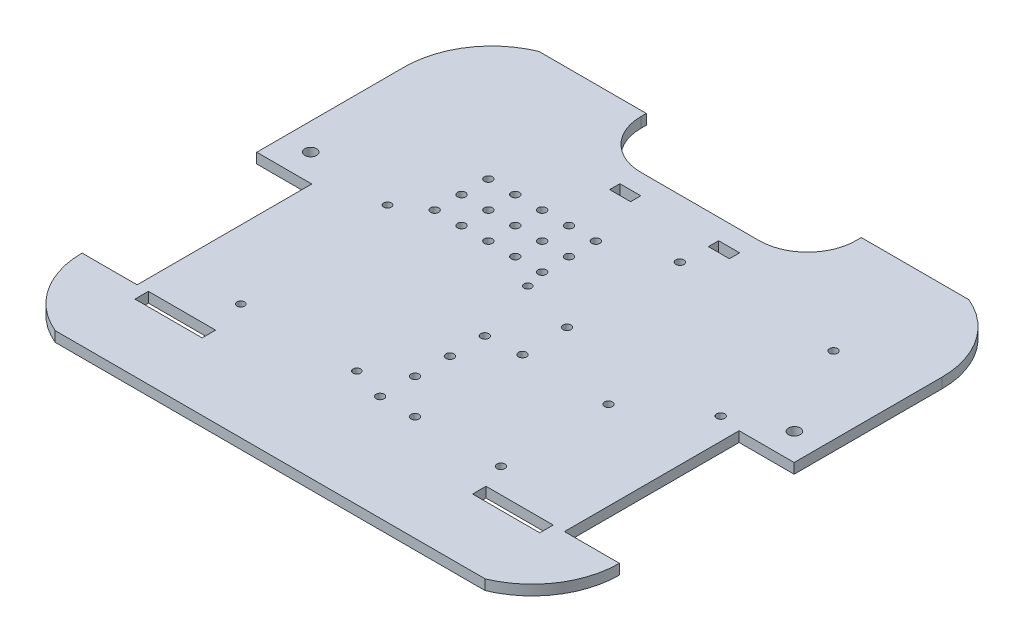
SolidWorks part; units mm, degrees
ref_plane "Front Plane" through (0, 0, 0) normal (0, 0, 1) x (1, 0, 0)
ref_plane "Top Plane" through (0, 0, 0) normal (0, 1, 0) x (1, 0, 0)
ref_plane "Right Plane" through (0, 0, 0) normal (1, 0, 0) x (0, 0, -1)
sketch "Sketch1" plane through (0, 0, 0) normal (0, 1, 0) x (1, 0, 0)
  line L1 (-127, 114.3) -> (127, 114.3)
  line L2 (-127, 114.3) -> (-127, -114.3)
  line L3 (-127, -114.3) -> (127, -114.3)
  line L4 (127, 114.3) -> (127, -114.3)
  line L5 (-127, 114.3) -> (127, -114.3) construction
  line L6 (-127, -114.3) -> (127, 114.3) construction
  point P0 (0, 0)
  dimension "D1" = 254
  dimension "D2" = 228.6
extrude "Boss-Extrude1" add sketch "Sketch1" along normal blind 4.826
sketch "Sketch2" plane through (0, 4.826, 0) normal (0, 1, 0) x (1, 0, 0)
  line L0 (-127, 114.3) -> (-127, -114.3) construction
  line L1 (-127, 6.35) -> (-101, 6.35)
  line L2 (-127, 6.35) -> (-127, -76.2)
  line L3 (-127, -76.2) -> (-101, -76.2)
  line L4 (-101, 6.35) -> (-101, -76.2)
  line L5 (127, -114.3) -> (127, 114.3) construction
  line L6 (127, 6.35) -> (101, 6.35)
  line L7 (127, 6.35) -> (127, -76.2)
  line L8 (127, -76.2) -> (101, -76.2)
  line L9 (101, 6.35) -> (101, -76.2)
  line L10 (-127, -114.3) -> (127, -114.3) construction
  dimension "D1" = 38.1
  dimension "D2" = 38.1
  dimension "D3" = 82.55
  dimension "D4" = 82.55
  dimension "D5" = 26
  dimension "D6" = 26
extrude "Cut-Extrude1" cut sketch "Sketch2" against normal blind 4.826
sketch "Sketch4" plane through (0, 4.826, 0) normal (0, 1, 0) x (1, 0, 0)
  line L0 (0, -114.3) -> (0, 114.3) construction
  line L1 (-127, -114.3) -> (127, -114.3) construction
  line L2 (127, 114.3) -> (-127, 114.3) construction
  line L3 (-127, 76.2) -> (-101.6, 76.2) construction
  line L4 (-127, 114.3) -> (-127, 6.35) construction
  line L5 (-101.6, 76.2) -> (-101.6, 114.3) construction
  line L6 (-127, 76.2) -> (-127, 114.3)
  line L7 (-127, 114.3) -> (-101.6, 114.3)
  line L8 (127, 76.2) -> (127, 114.3)
  line L9 (127, 114.3) -> (101.6, 114.3)
  arc A0 (-127, 76.2) -> (-101.6, 114.3) centre (-85.725, 76.2) cw
  arc A1 (127, 76.2) -> (101.6, 114.3) centre (85.725, 76.2) ccw
  dimension "D2" = 38.1
  dimension "D1" = 25.4
extrude "Cut-Extrude3" cut sketch "Sketch4" against normal blind 4.826
sketch "Sketch7" plane through (0, 4.826, 0) normal (0, 1, 0) x (1, 0, 0)
  line L0 (0, -114.3) -> (0, 114.3) construction
  line L1 (-127, -114.3) -> (127, -114.3) construction
  line L2 (101.6, 114.3) -> (-101.6, 114.3) construction
  line L3 (50.8, 88.9) -> (50.8, 114.3)
  line L4 (50.8, 88.9) -> (-50.8, 88.9)
  line L5 (0, 88.9) -> (0, 114.3)
  line L6 (50.8, 114.3) -> (-50.8, 114.3)
  line L7 (-50.8, 88.9) -> (-50.8, 114.3)
  line M6 (101.6, 114.3) -> (-101.6, 114.3)
  dimension "D1" = 25.4
  dimension "D2" = 50.8
extrude "Cut-Extrude5" cut sketch "Sketch7" against normal blind 4.826 contours L7 L4 L5 M6 | L5 L4 L3 M6
fillet "Fillet9" radius 22.86 1 edges at (-50.8, 2.413, -88.9)
fillet "Fillet10" radius 22.86 1 edges at (50.8, 2.413, -88.9)
sketch "Sketch8" plane through (0, 4.826, 0) normal (0, 1, 0) x (1, 0, 0)
  line L0 (-127, -76.2) -> (-101.6, -76.2) construction
  line L1 (-101.6, -76.2) -> (-101.6, -114.3) construction
  line L2 (-127, -114.3) -> (127, -114.3) construction
  line L3 (-127, -76.2) -> (-127, -114.3)
  line L4 (-127, -114.3) -> (-101.6, -114.3)
  line L5 (0, -114.3) -> (0, 88.9) construction
  line L6 (27.94, 88.9) -> (-27.94, 88.9) construction
  line L7 (127, -114.3) -> (101.6, -114.3)
  line L8 (127, -76.2) -> (127, -114.3)
  arc A0 (-127, -76.2) -> (-101.6, -114.3) centre (-85.725, -76.2) ccw
  arc A1 (127, -76.2) -> (101.6, -114.3) centre (85.725, -76.2) cw
  dimension "D1" = 25.4
extrude "Cut-Extrude6" cut sketch "Sketch8" against normal blind 4.826
sketch "Sketch9" plane through (0, 0, 0) normal (0, -1, 0) x (1, 0, 0)
  line L0 (-58.582, 76.2) -> (-101, 76.2) construction
  line L1 (-95.666, 76.2) -> (-63.916, 76.2)
  line L2 (-95.666, 76.2) -> (-95.666, 82.55)
  line L3 (-95.666, 82.55) -> (-63.916, 82.55)
  line L4 (-63.916, 76.2) -> (-63.916, 82.55)
  line L5 (-101, 76.2) -> (-95.666, 76.2) construction
  line L6 (-63.916, 76.2) -> (-58.582, 76.2) construction
  line L7 (0, 114.3) -> (0, -88.9) construction
  line L8 (-101.6, 114.3) -> (101.6, 114.3) construction
  line L9 (27.94, -88.9) -> (-27.94, -88.9) construction
  line L10 (63.916, 76.2) -> (58.582, 76.2) construction
  line L11 (101, 76.2) -> (95.666, 76.2) construction
  line L12 (63.916, 76.2) -> (63.916, 82.55)
  line L13 (95.666, 82.55) -> (63.916, 82.55)
  line L14 (95.666, 76.2) -> (95.666, 82.55)
  line L15 (95.666, 76.2) -> (63.916, 76.2)
  dimension "D1" = 31.75
  dimension "D2" = 6.35
extrude "Cut-Extrude7" cut sketch "Sketch9" against normal through all
sketch "Sketch11" plane through (0, 4.826, 0) normal (0, 1, 0) x (1, 0, 0)
  line L0 (-18.3929, 74.4508) -> (-28.2989, 74.4508) construction
  line L1 (-28.2989, 79.2768) -> (-28.2989, 74.4508) construction
  line L2 (-18.3929, 79.2768) -> (-28.2989, 79.2768) construction
  line L3 (-18.3929, 79.2768) -> (-18.3929, 74.4508) construction
  line L4 (28.2989, 74.4508) -> (18.3929, 74.4508) construction
  line L5 (18.3929, 79.2768) -> (18.3929, 74.4508) construction
  line L6 (28.2989, 79.2768) -> (18.3929, 79.2768) construction
  line L7 (28.2989, 79.2768) -> (28.2989, 74.4508) construction
  line L8 (-18.3929, 74.4508) -> (-28.2989, 74.4508)
  line L9 (-28.2989, 79.2768) -> (-28.2989, 74.4508)
  line L10 (-18.3929, 79.2768) -> (-28.2989, 79.2768)
  line L11 (-18.3929, 79.2768) -> (-18.3929, 74.4508)
  line L12 (28.2989, 74.4508) -> (18.3929, 74.4508)
  line L13 (18.3929, 79.2768) -> (18.3929, 74.4508)
  line L14 (28.2989, 79.2768) -> (18.3929, 79.2768)
  line L15 (28.2989, 79.2768) -> (28.2989, 74.4508)
extrude "Cut-Extrude8" cut sketch "Sketch11" against normal through all
sketch "Sketch13" plane through (0, 4.826, 0) normal (0, 1, 0) x (1, 0, 0)
  line L1 (-4.1249, -61.8428) -> (-4.1249, 17.9132) construction
  circle A0 centre (-10.4749, 24.7159) radius 1.905
  circle A1 centre (-23.1749, 24.7159) radius 1.905
  circle A2 centre (-35.8749, 24.7159) radius 1.905
  circle A3 centre (-48.5749, 24.7159) radius 1.905
  circle A4 centre (-61.2749, 24.7159) radius 1.905
  circle A5 centre (-23.1749, 37.4159) radius 1.905
  circle A6 centre (-35.8749, 37.4159) radius 1.905
  circle A7 centre (-48.5749, 37.4159) radius 1.905
  circle A8 centre (-61.2749, 37.4159) radius 1.905
  circle A9 centre (-23.1749, 50.1159) radius 1.905
  circle A10 centre (-35.8749, 50.1159) radius 1.905
  circle A11 centre (-48.5749, 50.1159) radius 1.905
  circle A12 centre (-61.2749, 50.1159) radius 1.905
  circle A13 centre (-10.4749, 37.4159) radius 1.905
  circle A14 centre (-10.4749, 50.1159) radius 1.905
  dimension "D1" = 3.81
  dimension "D4" = 6.35
  dimension "D2" = 5
  dimension "D3" = 3
extrude "Cut-Extrude10" cut sketch "Sketch13" against normal through all
sketch "Sketch14" plane through (0, 4.826, 0) normal (0, 1, 0) x (1, 0, 0)
  circle A0 centre (-68.6409, -59.5568) radius 1.778 construction
  circle A1 centre (-13.7769, -59.5568) radius 1.778 construction
  circle A2 centre (-74.4829, 15.6272) radius 1.778 construction
  circle A3 centre (-8.1889, 15.6272) radius 1.778 construction
  circle A4 centre (-68.6409, -59.5568) radius 1.778
  circle A5 centre (-13.7769, -59.5568) radius 1.778
  circle A6 centre (-74.4829, 15.6272) radius 1.778
  circle A7 centre (-8.1889, 15.6272) radius 1.778
extrude "Cut-Extrude11" cut sketch "Sketch14" against normal through all
sketch "Sketch15" plane through (0, 4.826, 0) normal (0, 1, 0) x (1, 0, 0)
  circle A0 centre (59.2769, -64.4851) radius 1.905 construction
  circle A1 centre (18.6369, -64.4851) radius 1.905 construction
  circle A2 centre (59.2769, -13.6851) radius 1.905 construction
  circle A3 centre (18.6369, -13.6851) radius 1.905 construction
  circle A4 centre (59.2769, -64.4851) radius 1.905
  circle A5 centre (18.6369, -64.4851) radius 1.905
  circle A6 centre (59.2769, -13.6851) radius 1.905
  circle A7 centre (18.6369, -13.6851) radius 1.905
extrude "Cut-Extrude12" cut sketch "Sketch15" against normal through all
sketch "Sketch16" plane through (0, 4.826, 0) normal (0, 1, 0) x (1, 0, 0)
  circle A0 centre (90.6459, 7.9994) radius 1.905 construction
  circle A1 centre (18.0019, 7.9994) radius 1.905 construction
  circle A2 centre (18.0019, 61.3394) radius 1.905 construction
  circle A3 centre (90.6459, 61.3394) radius 1.905 construction
  circle A4 centre (90.6459, 7.9994) radius 1.905
  circle A5 centre (18.0019, 7.9994) radius 1.905
  circle A6 centre (18.0019, 61.3394) radius 1.905
  circle A7 centre (90.6459, 61.3394) radius 1.905
extrude "Cut-Extrude13" cut sketch "Sketch16" against normal through all
sketch "Sketch17" plane through (0, 0, 0) normal (0, -1, 0) x (1, 0, 0)
  circle A0 centre (114.3, -19.1646) radius 2.7781 construction
  circle A1 centre (-114.3, -19.1646) radius 2.7781 construction
  circle A2 centre (114.3, -19.1646) radius 2.7781
  circle A3 centre (-114.3, -19.1646) radius 2.7781
extrude "Cut-Extrude14" cut sketch "Sketch17" against normal through all
sketch "Sketch18" plane through (0, 4.826, 0) normal (0, 1, 0) x (1, 0, 0)
  circle A0 centre (2.1269, -64.4851) radius 1.905
  circle A1 centre (18.6369, -64.4851) radius 1.905 construction
  circle A2 centre (2.1269, -47.9751) radius 1.905
  circle A3 centre (2.1269, -31.4651) radius 1.905
  circle A4 centre (2.1269, -14.9551) radius 1.905
  dimension "D1" = 3.81
  dimension "D2" = 16.51
  dimension "D3" = 0
  dimension "D4" = 4
extrude "Cut-Extrude15" cut sketch "Sketch18" against normal through all
equation "\"MDF\"= 0.19in"
equation "\"GenDiameter\"= 60mm"
equation "\"GenCutDiameter\" = 1.8in"
equation "\"GenCutDistance\" = 1"
equation "\"TowerHeight\" = 6in"
equation "\"TowerFrontBase\" = 3in"
equation "\"FunnelHeight\" = 1in"
equation "\"FunnelAngle\" = 20"
equation "\"TowerSideBase\" = 3in"
equation "\"BaseLength\" = 9in"
equation "\"BaseWidth\" = 10in"
equation "\"WheelHoleLength\" = 3.25in"
equation "\"WheelHoleWidth\" = 26mm"
equation "\"DropLength\" = 1in"
equation "\"D1@Sketch1\"=\"BaseWidth\""
equation "\"D2@Sketch1\"=\"BaseLength\""
equation "\"D1@Boss-Extrude1\"=\"MDF\""
equation "\"WheelHoleFromBack\" = 1.5in"
equation "\"D1@Sketch2\"=\"WheelHoleFromBack\""
equation "\"D2@Sketch2\"=\"WheelHoleFromBack\""
equation "\"D3@Sketch2\"=\"WheelHoleLength\""
equation "\"D4@Sketch2\"=\"WheelHoleLength\""
equation "\"D5@Sketch2\"=\"WheelHoleWidth\""
equation "\"D6@Sketch2\"=\"WheelHoleWidth\""
equation "\"D1@Cut-Extrude1\"=\"MDF\""
equation "\"DropWidth\" = 8.5in"
equation "\"BumperWidth\" = 1in"
equation "\"D1@Sketch4\"=\"BumperWidth\""
equation "\"D2@Sketch4\"=\"WheelHoleFromBack\""
equation "\"D1@Cut-Extrude3\"=\"MDF\""
equation "\"D1@Sketch7\"=\"DropLength\""
equation "\"D2@Sketch7\"=\"DropWidthTop\"/2"
equation "\"D1@Cut-Extrude5\"=\"MDF\""
equation "\"D1@Sketch8\"=\"BumperWidth\""
equation "\"D1@Cut-Extrude6\"=\"MDF\""
equation "\"DropWidthTop\" = 4in"
